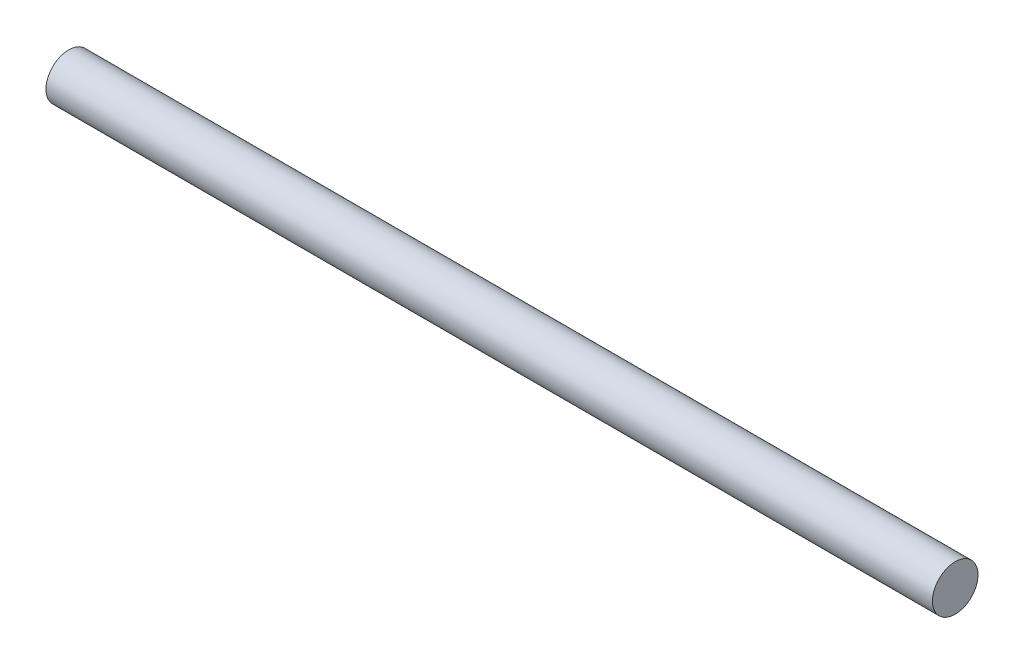
SolidWorks part; units mm, degrees
material "Copper"
ref_plane "Front Plane" through (0, 0, 0) normal (0, 0, 1) x (1, 0, 0)
ref_plane "Top Plane" through (0, 0, 0) normal (0, 1, 0) x (1, 0, 0)
ref_plane "Right Plane" through (0, 0, 0) normal (1, 0, 0) x (0, 0, -1)
sketch "Sketch1" plane through (0, 0, 0) normal (1, 0, 0) x (0, 0, -1)
  circle A0 centre (0, 0) radius 0.2921
  dimension "D1" = 0.5842
extrude "Boss-Extrude1" add sketch "Sketch1" along normal blind 11.37
